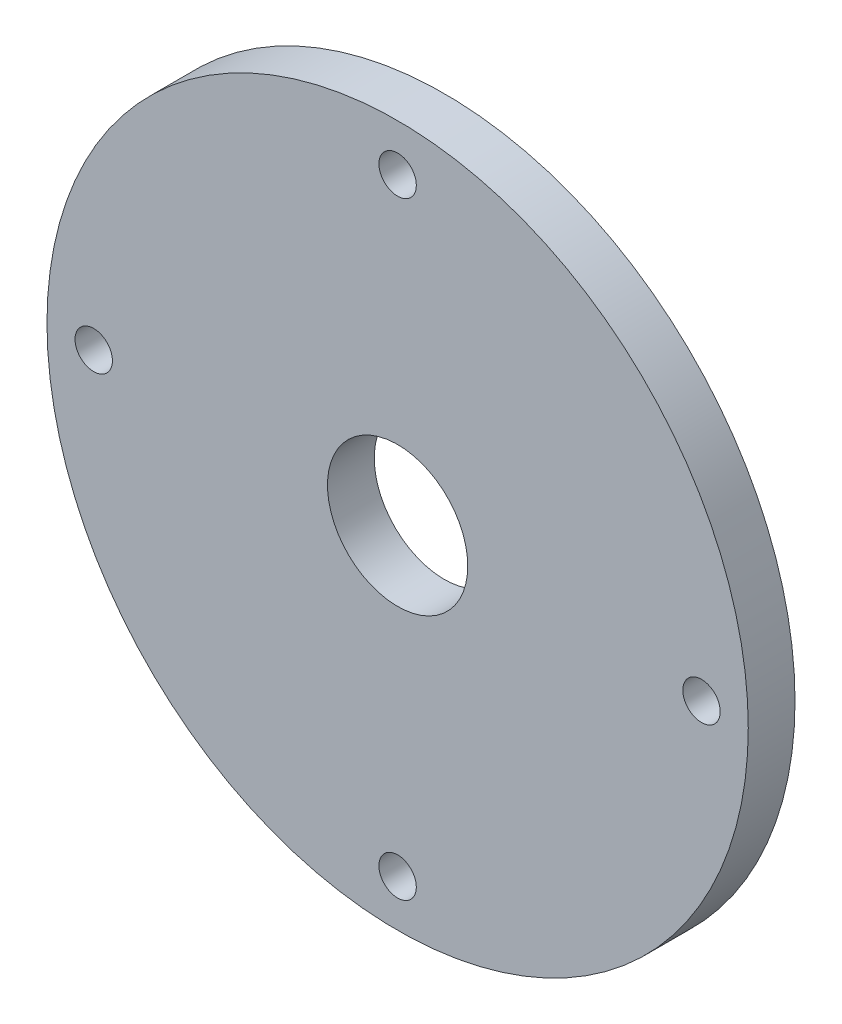
SolidWorks part; units mm, degrees
ref_plane "Front Plane" through (0, 0, 0) normal (0, 0, 1) x (1, 0, 0)
ref_plane "Top Plane" through (0, 0, 0) normal (0, 1, 0) x (1, 0, 0)
ref_plane "Right Plane" through (0, 0, 0) normal (1, 0, 0) x (0, 0, -1)
sketch "Sketch1" plane through (0, 0, 0) normal (0, 0, 1) x (1, 0, 0)
  circle A3 centre (0, 0) radius 15
  circle A4 centre (0, 0) radius 75 construction
  circle A5 centre (0, 0) radius 75
  circle A6 centre (0, 65) radius 4 construction
  circle A7 centre (0, 65) radius 4
  circle A8 centre (-65, 0) radius 4 construction
  circle A9 centre (0, -65) radius 4 construction
  circle A10 centre (65, 0) radius 4 construction
  circle A11 centre (-65, 0) radius 4
  circle A12 centre (0, -65) radius 4
  circle A13 centre (65, 0) radius 4
extrude "Boss-Extrude1" add sketch "Sketch1" along normal blind 10
